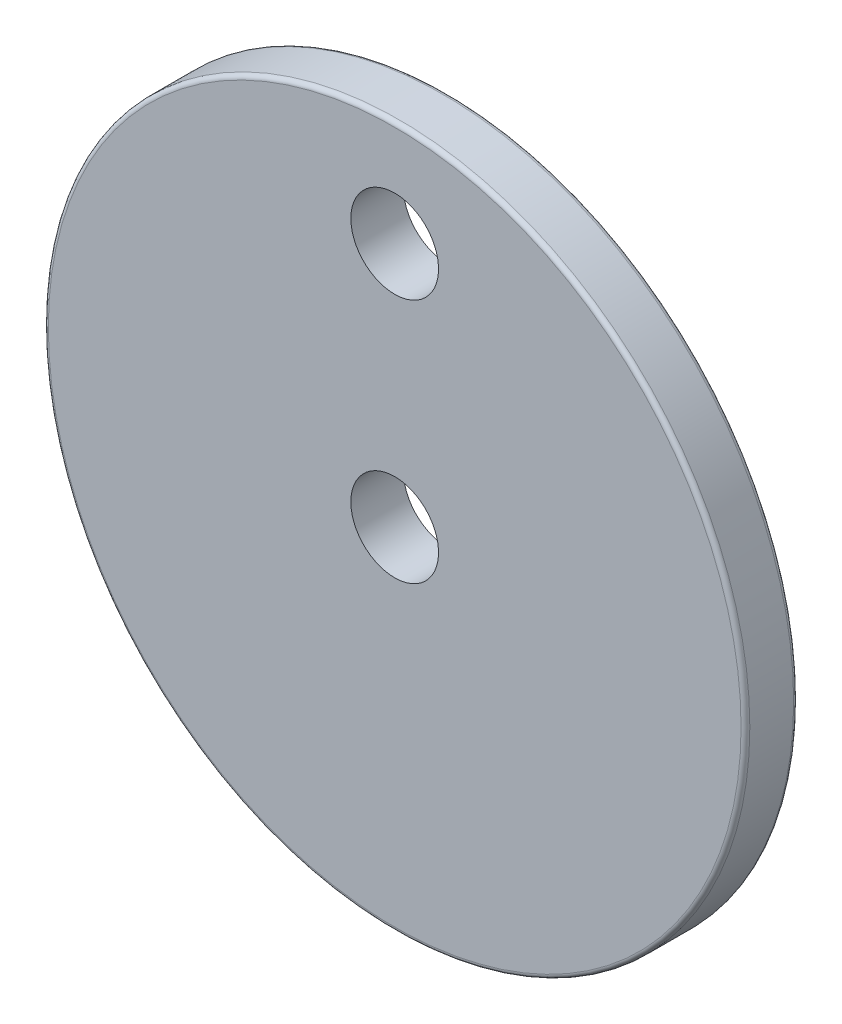
SolidWorks part; units mm, degrees
ref_plane "Front Plane" through (0, 0, 0) normal (0, 0, 1) x (1, 0, 0)
ref_plane "Top Plane" through (0, 0, 0) normal (0, 1, 0) x (1, 0, 0)
ref_plane "Right Plane" through (0, 0, 0) normal (1, 0, 0) x (0, 0, -1)
sketch "Sketch1" plane through (0, 0, 0) normal (0, 0, 1) x (1, 0, 0)
  line L0 (0, 0) -> (0, 355.6) construction
  circle A0 centre (0, 0) radius 508
  circle A1 centre (0, 0) radius 63.5
  circle A2 centre (0, 355.6) radius 63.5
  dimension "D1" = 1016
  dimension "D2" = 127
  dimension "D4" = 127
  dimension "D3" = 355.6
extrude "Boss-Extrude1" add sketch "Sketch1" along normal mid plane 76.2
fillet "Fillet1" radius 6.35 2 edges at (508, 0, -38.1) (508, 0, 38.1)
